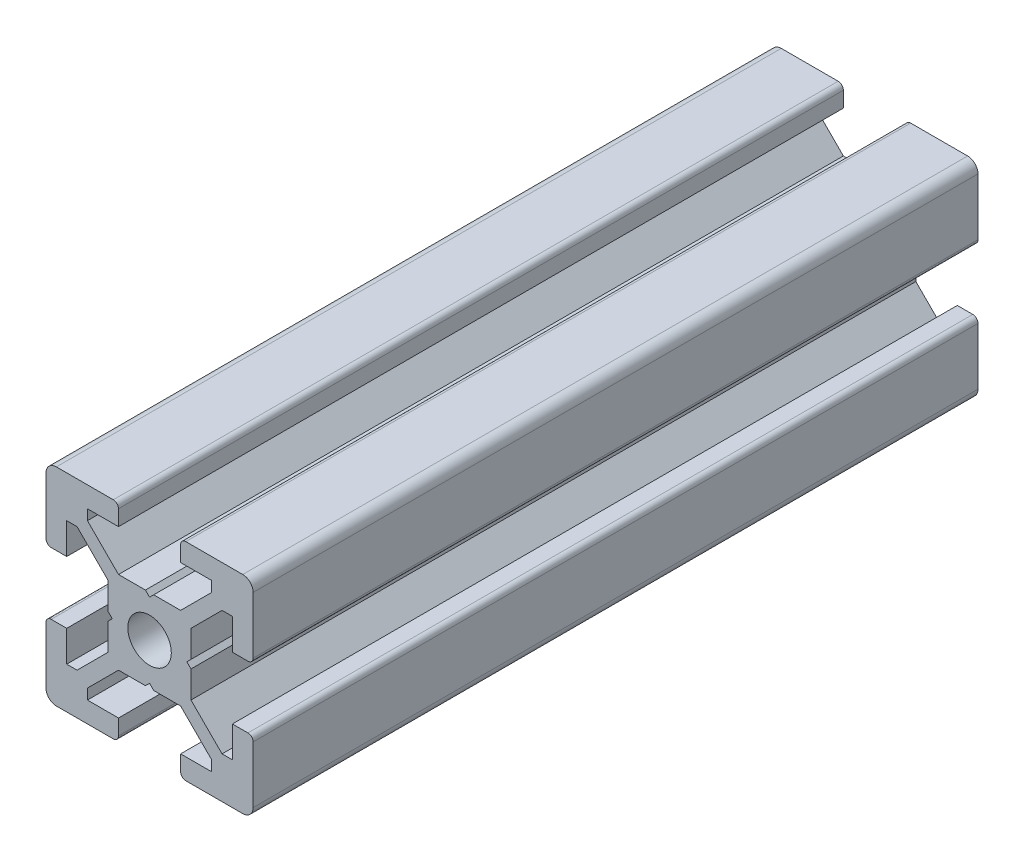
SolidWorks part; units mm, degrees
material "Lega 6061"
ref_plane "Piano frontale" through (0, 0, 0) normal (0, 0, 1) x (1, 0, 0)
ref_plane "Piano superiore" through (0, 0, 0) normal (0, 1, 0) x (1, 0, 0)
ref_plane "Piano destro" through (0, 0, 0) normal (1, 0, 0) x (0, 0, -1)
sketch "Schizzo1" plane through (0, 0, 0) normal (0, 0, 1) x (1, 0, 0)
  line L0 (0, 0) -> (-10, 0) construction
  line L1 (0, 0) -> (0, 10) construction
  line L2 (-3.6, 0) -> (-4, 0.4)
  line L3 (-4, 0.4) -> (-4, 3)
  line L4 (-4, 3) -> (-7, 6)
  line L5 (-7, 6) -> (-8, 6)
  line L6 (-8, 6) -> (-8, 3)
  line L7 (-8, 3) -> (-9.5, 3)
  line L8 (-10, 3.5) -> (-10, 9)
  line L9 (0, 0) -> (-10, 10) construction
  line L10 (0, 3.6) -> (-0.4, 4)
  line L11 (-0.4, 4) -> (-3, 4)
  line L12 (-3, 4) -> (-6, 7)
  line L13 (-6, 7) -> (-6, 8)
  line L14 (-6, 8) -> (-3, 8)
  line L15 (-3, 8) -> (-3, 9.5)
  line L16 (-3.5, 10) -> (-9, 10)
  line L17 (0, 0) -> (-10, -10) construction
  line L18 (-3.5, -10) -> (-9, -10)
  line L19 (-3, -8) -> (-3, -9.5)
  line L20 (-6, -8) -> (-3, -8)
  line L21 (-6, -7) -> (-6, -8)
  line L22 (-3, -4) -> (-6, -7)
  line L23 (-0.4, -4) -> (-3, -4)
  line L24 (0, -3.6) -> (-0.4, -4)
  line L25 (-10, -3.5) -> (-10, -9)
  line L26 (-8, -3) -> (-9.5, -3)
  line L27 (-8, -6) -> (-8, -3)
  line L28 (-7, -6) -> (-8, -6)
  line L29 (-4, -3) -> (-7, -6)
  line L30 (-4, -0.4) -> (-4, -3)
  line L31 (-3.6, 0) -> (-4, -0.4)
  line L32 (0, 0) -> (10, -10) construction
  line L33 (0, 0) -> (10, 10) construction
  line L34 (3.6, 0) -> (4, -0.4)
  line L35 (4, -0.4) -> (4, -3)
  line L36 (4, -3) -> (7, -6)
  line L37 (7, -6) -> (8, -6)
  line L38 (8, -6) -> (8, -3)
  line L39 (8, -3) -> (9.5, -3)
  line L40 (10, -3.5) -> (10, -9)
  line L41 (0, -3.6) -> (0.4, -4)
  line L42 (0.4, -4) -> (3, -4)
  line L43 (3, -4) -> (6, -7)
  line L44 (6, -7) -> (6, -8)
  line L45 (6, -8) -> (3, -8)
  line L46 (3, -8) -> (3, -9.5)
  line L47 (3.5, -10) -> (9, -10)
  line L48 (3.5, 10) -> (9, 10)
  line L49 (3, 8) -> (3, 9.5)
  line L50 (6, 8) -> (3, 8)
  line L51 (6, 7) -> (6, 8)
  line L52 (3, 4) -> (6, 7)
  line L53 (0.4, 4) -> (3, 4)
  line L54 (0, 3.6) -> (0.4, 4)
  line L55 (10, 3.5) -> (10, 9)
  line L56 (8, 3) -> (9.5, 3)
  line L57 (8, 6) -> (8, 3)
  line L58 (7, 6) -> (8, 6)
  line L59 (4, 3) -> (7, 6)
  line L60 (4, 0.4) -> (4, 3)
  line L61 (3.6, 0) -> (4, 0.4)
  arc A0 (-10, 9) -> (-9, 10) centre (-9, 9) cw
  arc A1 (-3, 9.5) -> (-3.5, 10) centre (-3.5, 9.5) ccw
  arc A2 (-9.5, 3) -> (-10, 3.5) centre (-9.5, 3.5) cw
  arc A3 (-9.5, -3) -> (-10, -3.5) centre (-9.5, -3.5) ccw
  arc A4 (-3, -9.5) -> (-3.5, -10) centre (-3.5, -9.5) cw
  arc A5 (-10, -9) -> (-9, -10) centre (-9, -9) ccw
  arc A6 (10, -9) -> (9, -10) centre (9, -9) cw
  arc A7 (3, -9.5) -> (3.5, -10) centre (3.5, -9.5) ccw
  arc A8 (9.5, -3) -> (10, -3.5) centre (9.5, -3.5) cw
  arc A9 (9.5, 3) -> (10, 3.5) centre (9.5, 3.5) ccw
  arc A10 (3, 9.5) -> (3.5, 10) centre (3.5, 9.5) cw
  arc A11 (10, 9) -> (9, 10) centre (9, 9) ccw
  circle A12 centre (0, 0) radius 2.1
  point P24 (-3, 10)
  point P27 (-10, 3)
  point P49 (-10, -3)
  point P50 (-3, -10)
  point P92 (3, -10)
  point P93 (10, -3)
  point P94 (10, 3)
  point P95 (3, 10)
  dimension "D2" = 1
  dimension "D12" = 0.5
  dimension "D13" = 4.2
  dimension "D3" = 8
  dimension "D4" = 0.4
  dimension "D5" = 45
  dimension "D6" = 6
  dimension "D7" = 12
  dimension "D8" = 20
  dimension "D9" = 2
  dimension "D10" = 4
  dimension "D11" = 45
extrude "Estrusione-Estrusione1" add sketch "Schizzo1" along normal blind 70
